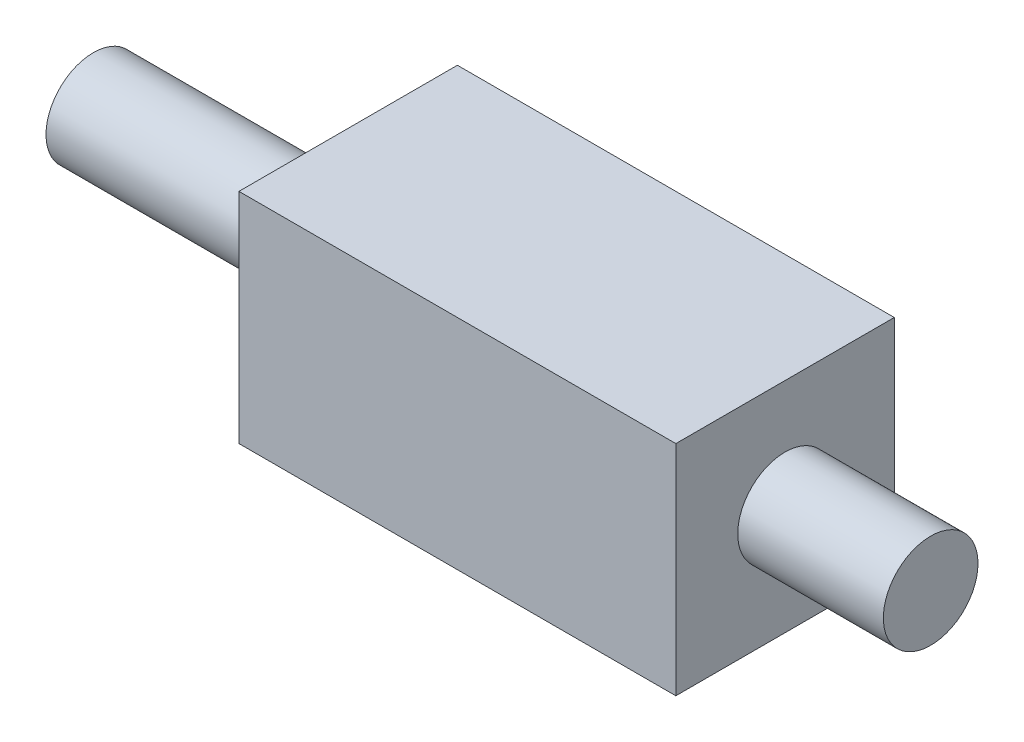
SolidWorks part; units mm, degrees
ref_plane "Front" through (0, 0, 0) normal (0, 0, 1) x (1, 0, 0)
ref_plane "Top" through (0, 0, 0) normal (0, 1, 0) x (1, 0, 0)
ref_plane "Right" through (0, 0, 0) normal (1, 0, 0) x (0, 0, -1)
sketch "Croquis1" plane through (0, 0, 0) normal (1, 0, 0) x (0, 0, -1)
  line L1 (1.5, -1) -> (-1.5, -1)
  line L2 (1.5, -1) -> (1.5, 2)
  line L3 (1.5, 2) -> (-1.5, 2)
  line L4 (-1.5, -1) -> (-1.5, 2)
  line L5 (1.5, -1) -> (-1.5, 2) construction
  line L6 (1.5, 2) -> (-1.5, -1) construction
  dimension "D1" = 3
extrude "Saliente-Extruir1" add sketch "Croquis1" along normal blind 6
sketch "Croquis2" plane through (0, 0, 0) normal (-1, 0, 0) x (0, 0, 1)
  circle A0 centre (0, 0.5) radius 0.65
  dimension "D1" = 1.3
extrude "Saliente-Extruir2" add sketch "Croquis2" along normal blind 3.5
sketch "Croquis6" plane through (6, 0, 0) normal (1, 0, 0) x (0, 0, -1)
  circle A0 centre (0, 0.5) radius 0.65
  dimension "D1" = 1.3
extrude "Saliente-Extruir3" add sketch "Croquis6" along normal blind 2
